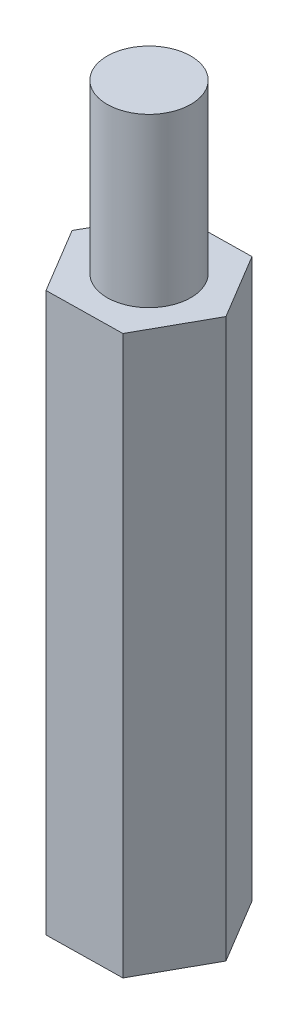
SolidWorks part; units mm, degrees
material "黄铜"
ref_plane "前视基准面" through (0, 0, 0) normal (0, 0, 1) x (1, 0, 0)
ref_plane "上视基准面" through (0, 0, 0) normal (0, 1, 0) x (1, 0, 0)
ref_plane "右视基准面" through (0, 0, 0) normal (1, 0, 0) x (0, 0, -1)
sketch "草图1" plane through (0, 0, 0) normal (0, 1, 0) x (1, 0, 0)
  line L0 (-5.8996, -0.071) -> (5.5773, 0.1142) construction
  line L1 (1.3945, -2.3278) -> (2.7132, 0.0438)
  line L2 (2.7132, 0.0438) -> (1.3187, 2.3716)
  line L3 (1.3187, 2.3716) -> (-1.3945, 2.3278)
  line L4 (-1.3945, 2.3278) -> (-2.7132, -0.0438)
  line L5 (-2.7132, -0.0438) -> (-1.3187, -2.3716)
  line L6 (-1.3187, -2.3716) -> (1.3945, -2.3278)
  circle A0 centre (0, 0) radius 2.35 construction
  circle A1 centre (0, 0) radius 1.5
  dimension "D3" = 3
  dimension "D1" = 4.7
  dimension "D2" = 60
extrude "凸台-拉伸1" add sketch "草图1" along normal blind 20
sketch "草图2" plane through (0, 20, 0) normal (0, 1, 0) x (1, 0, 0)
  circle A0 centre (0, 0) radius 1.5
  dimension "D1" = 3
extrude "凸台-拉伸2" add sketch "草图2" along normal blind 6 separate body
